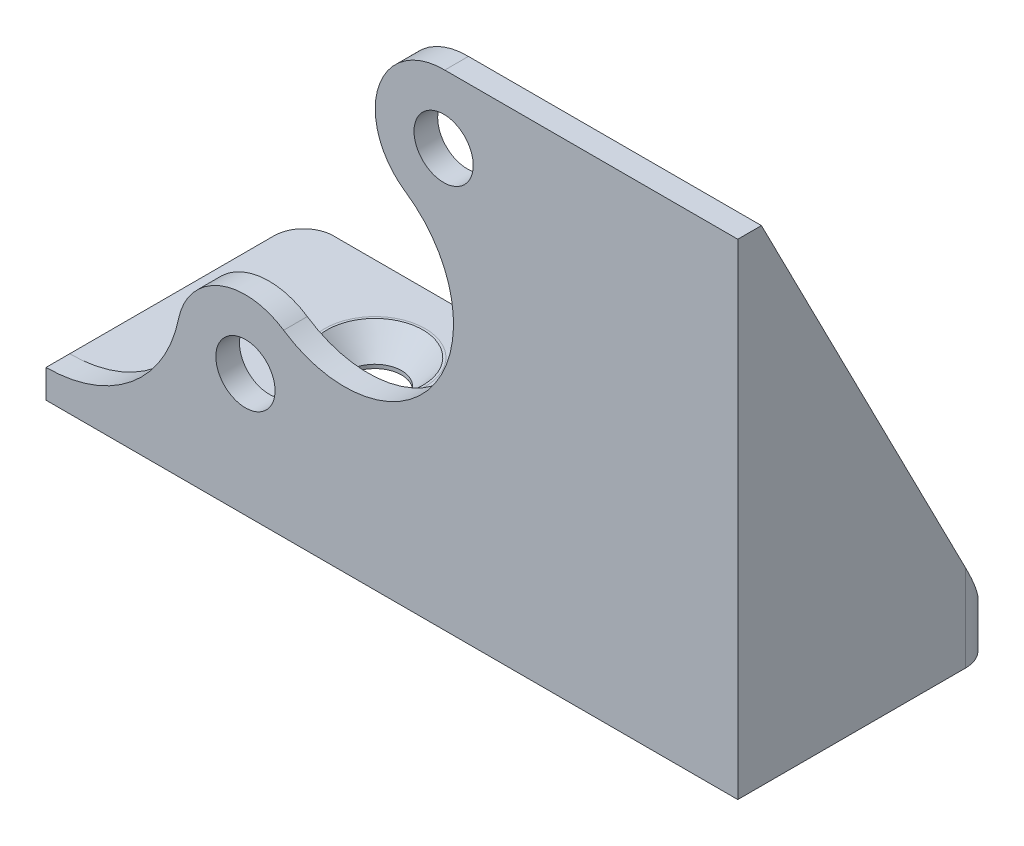
SolidWorks part; units mm, degrees
material "UNS A97075 7075-T651 2.501–3.000 in plate (F_ty = 56 ksi)"
ref_plane "Front Plane" through (0, 0, 0) normal (0, 0, 1) x (1, 0, 0)
ref_plane "Top Plane" through (0, 0, 0) normal (0, 1, 0) x (1, 0, 0)
ref_plane "Right Plane" through (0, 0, 0) normal (1, 0, 0) x (0, 0, -1)
sketch "Sketch2" plane through (0, 0, 0) normal (0, 0, 1) x (1, 0, 0)
  line L1 (0, 0) -> (101.6, 0)
  line L2 (0, 0) -> (0, 127)
  line L3 (0, 127) -> (101.6, 127)
  line L4 (101.6, 0) -> (101.6, 127)
  dimension "D1" = 101.6
  dimension "D2" = 127
extrude "Boss-Extrude1" add sketch "Sketch2" along normal blind 3.175
sketch "Sketch3" [suppressed] plane through (0, 0, 3.175) normal (0, 0, 1) x (1, 0, 0)
  line L0 (101.6, 0) -> (101.6, 127) construction
  line L1 (0, 0) -> (101.6, 0)
  line L2 (0, 0) -> (0, 12.1088)
  line L3 (0, 12.1088) -> (101.6, 12.1088)
  line L4 (101.6, 0) -> (101.6, 12.1088)
extrude "Boss-Extrude2" [suppressed] add sketch "Sketch3" along normal blind 25.4
sketch "Sketch5" plane through (0, 0, 0) normal (0, 0, -1) x (-1, 0, 0)
  line L0 (-58.5712, 65.1526) -> (-81.5862, 65.1526)
  line L1 (-81.5862, 0) -> (-97.9068, 0)
  line L2 (-81.5862, 0) -> (-5.0343, 0)
  line L3 (-5.0343, 0) -> (-5.0343, 3.81)
  line L4 (0, 0) -> (-101.6, 0) construction
  line L5 (-81.5862, 0) -> (-81.5862, 65.1526) construction
  line L6 (-97.9068, 0) -> (-97.9068, 65.1526)
  line L7 (-97.9068, 65.1526) -> (-81.5862, 65.1526)
  line L8 (0, 127) -> (0, 0) construction
  line L9 (-4.9708, 0.0028) -> (-4.9708, -2.9972) construction
  line L10 (-101.6, 0) -> (-101.6, 127) construction
  line L11 (-97.9708, -2.9972) -> (-97.9708, 0.0028) construction
  circle A12 centre (-58.4162, 55.9739) radius 3.9751
  arc A13 (-53.2878, 48.36) -> (-58.5712, 65.1526) centre (-58.4162, 55.9739) ccw
  arc A14 (-53.2878, 48.36) -> (-36.9387, 24.0877) centre (-45.1132, 36.2238) ccw
  arc A15 (-22.8172, 18.3173) -> (-36.9387, 24.0877) centre (-31.8102, 16.4738) ccw
  circle A16 centre (-31.8102, 16.4738) radius 3.9751
  arc A17 (-5.0343, 3.81) -> (-22.8172, 18.3173) centre (-5.0343, 21.9627) cw
  line M8 (0, 0) -> (0, 127)
  line M9 (0, 127) -> (-101.6, 127)
  line M10 (-101.6, 127) -> (-101.6, 0)
  line M11 (-101.6, 0) -> (0, 0)
  dimension "D1" = 3.81
  dimension "D2" = 76.5519
  dimension "D3" = 92.8726
  dimension "D5" = 5.0343
  dimension "D6" = 0.0635
  dimension "D7" = 3.6932
  dimension "D8" = 0.0639
extrude "Cut-Extrude1" cut sketch "Sketch5" against normal blind 3.175 contours A17 L3 L6 L7 L0 A13 A14 A15 M11 M8 M9 M10 | A12 | A16
sketch "Sketch10" plane through (5.0343, 0, 0) normal (1, 0, 0) x (0, 0, -1)
  line L0 (-3.175, 0) -> (-4.2418, 0)
  line L1 (-4.2418, 0) -> (-4.2418, -2.9972)
  line L2 (-4.2418, -2.9972) -> (-34.5948, -2.9972)
  line L3 (-34.5948, -2.9972) -> (-34.5948, 0)
  line L4 (-34.5948, 0) -> (-4.2418, 0) construction
  line L7 (-3.175, 3.81) -> (-34.5948, 3.81)
  line L8 (-3.175, 3.81) -> (-3.175, 0)
  line L9 (-34.5948, 3.81) -> (-34.5948, 0)
  dimension "D1" = 1.0668
  dimension "D2" = 2.9972
  dimension "D3" = 30.353
  dimension "D4" = 3.81
extrude "Boss-Extrude3" add sketch "Sketch10" along normal up to surface (92.8726 mm away) up to face at (97.9068, 32.5763, 1.5875)
sketch "Sketch11" plane through (97.9068, 0, 0) normal (1, 0, 0) x (0, 0, -1)
  line L1 (-3.175, 3.81) -> (-34.5948, 3.81) construction
  line L3 (-3.175, 65.1526) -> (-3.175, 3.81)
  line L6 (-34.5948, 3.81) -> (-3.175, 3.81)
  line L8 (-34.5948, 3.81) -> (-3.175, 3.81) construction
  line L9 (-34.5948, 3.81) -> (-3.175, 65.1526)
extrude "Boss-Extrude4" add sketch "Sketch11" against normal blind 6.35
sketch "Sketch18" plane through (0, -2.9972, 0) normal (0, -1, 0) x (1, 0, 0)
  circle A2 centre (25.968, 23.2283) radius 3.175
  circle A4 centre (81.868, 23.2283) radius 3.175
extrude "Cut-Extrude3" cut sketch "Sketch18" against normal up to surface (6.8072 mm away) up to face at (48.2956, 3.81, 18.8849)
fillet "Fillet4" radius 4.0005 4 edges at (97.9068, -1.4986, 4.2418) (5.0343, -1.4986, 4.2418) (97.9068, 0.4064, 34.5948) (5.0343, 0.4064, 34.5948)
sketch "Sketch19" plane through (0, 0, 34.5948) normal (0, 0, 1) x (1, 0, 0)
  line L0 (9.0348, 0.0028) -> (93.9063, 0.0028)
  line L1 (9.0348, 3.81) -> (9.0348, -2.9972) construction
  line L2 (93.9063, -2.9972) -> (93.9063, 3.81) construction
  line L3 (93.9063, -2.9972) -> (9.0348, -2.9972) construction
  dimension "D1" = 3
sketch "Sketch20" plane through (97.9068, 0, 0) normal (1, 0, 0) x (0, 0, -1)
  line L0 (-8.2423, 0) -> (-30.7225, 0)
sketch "Sketch22" plane through (5.0343, 0, 0) normal (-1, 0, 0) x (0, 0, 1)
  line L0 (8.2423, 0) -> (30.5943, 0)
  line L1 (30.5943, -2.9972) -> (30.5943, 3.81) construction
fillet "Fillet5" [suppressed] radius 6.35
split line "Split Line1"
split line "Split Line4"
split line "Split Line5"
fillet "Fillet6" [suppressed] radius 6.35
mirror "Mirror5" about plane through (0, 0, 0) normal (0, 0, 1) of bodies 114
sketch "FEA Force Line" plane through (0, 0, -3.175) normal (0, 0, -1) x (-1, 0, 0)
  line L0 (-58.4162, 55.9739) -> (-31.8102, 16.4738)
  line L1 (-45.1132, 36.2238) -> (-57.2494, 28.0493)
  circle A0 centre (-58.4162, 55.9739) radius 3.9751 construction
  circle A2 centre (-31.8102, 16.4738) radius 3.9751 construction
  arc A3 (-53.2878, 48.36) -> (-36.9387, 24.0877) centre (-45.1132, 36.2238) ccw construction
ref_plane "Plane1" through (14.2491, -9.5978, 0) normal (0.8294, -0.5587, 0) x (-0.5587, -0.8294, 0)
ref_plane "Plane2" through (30.8641, 45.8216, 0) normal (0.5587, 0.8294, 0) x (0.8294, -0.5587, 0)
sketch "Sketch25" plane through (0, 0, 0) normal (0, 0, 1) x (1, 0, 0)
  line L0 (105.4755, -15.2416) -> (106.8408, 71.8338)
  line L1 (105.4755, -15.2416) -> (-9.9073, -13.4325)
  line L2 (106.8408, 71.8338) -> (-8.542, 73.6429)
  line L3 (-9.9073, -13.4325) -> (-8.542, 73.6429)
extrude "Cut-Extrude4" cut sketch "Sketch25" along normal up to surface (34.5948 mm away) up to face at (51.4706, -1.4972, 34.5948)
sketch "Sketch28" plane through (0, -2.9972, 0) normal (0, -1, 0) x (1, 0, 0)
  line L4 (5.0343, -8.2423) -> (5.0343, -30.5943)
  line L6 (9.0348, -34.5948) -> (93.9063, -34.5948)
  line L7 (93.9063, -4.2418) -> (9.0348, -4.2418)
  line L11 (93.9063, -4.2418) -> (9.0348, -4.2418)
  line L13 (97.9068, -30.5943) -> (97.9068, -8.2423)
  line L15 (9.0348, -34.5948) -> (93.9063, -34.5948)
  line L16 (5.0343, -8.2423) -> (5.0343, -30.5943)
  line L17 (97.9068, -30.5943) -> (97.9068, -8.2423)
  arc A5 (5.0343, -30.5943) -> (9.0348, -34.5948) centre (9.0348, -30.5943) ccw
  arc A6 (5.0343, -30.5943) -> (9.0348, -34.5948) centre (9.0348, -30.5943) ccw
  arc A7 (93.9063, -34.5948) -> (97.9068, -30.5943) centre (93.9063, -30.5943) ccw
  arc A12 (93.9063, -34.5948) -> (97.9068, -30.5943) centre (93.9063, -30.5943) ccw
  arc A13 (97.9068, -8.2423) -> (93.9063, -4.2418) centre (93.9063, -8.2423) ccw
  arc A14 (97.9068, -8.2423) -> (93.9063, -4.2418) centre (93.9063, -8.2423) ccw
  arc A15 (9.0348, -4.2418) -> (5.0343, -8.2423) centre (9.0348, -8.2423) ccw
  arc A16 (9.0348, -4.2418) -> (5.0343, -8.2423) centre (9.0348, -8.2423) ccw
  dimension "D1" = 0
extrude "Cut-Extrude5" cut sketch "Sketch28" against normal up to surface (2.9972 mm away) up to face at (51.4706, 0, -3.8852)
sketch "Sketch31" plane through (0, 3.81, 0) normal (0, 1, 0) x (1, 0, 0)
  line L4 (91.5568, 34.5948) -> (9.0348, 34.5948)
  line L6 (5.0343, 30.5943) -> (5.0343, 3.175)
  line L12 (5.0343, 30.5943) -> (5.0343, 3.175)
  line L14 (5.0343, 3.175) -> (91.5568, 3.175)
  line L16 (91.5568, 34.5948) -> (9.0348, 34.5948)
  line L22 (5.0343, 3.175) -> (91.5568, 3.175)
  line L24 (91.5568, 3.175) -> (91.5568, 34.5948)
  line L25 (91.5568, 3.175) -> (91.5568, 34.5948)
  circle A0 centre (81.868, 23.2283) radius 3.175 construction
  arc A1 (9.0348, 34.5948) -> (5.0343, 30.5943) centre (9.0348, 30.5943) ccw
  arc A3 (9.0348, 34.5948) -> (5.0343, 30.5943) centre (9.0348, 30.5943) ccw
  circle A4 centre (25.968, 23.2283) radius 3.175 construction
  circle A5 centre (81.868, 23.2283) radius 3.175
  circle A6 centre (25.968, 23.2283) radius 3.175
  dimension "D1" = 0
fillet "Fillet7" radius 6.35 1 edges at (91.5568, 3.81, -18.8849)
sketch "Sketch33" plane through (0, 3.81, 0) normal (0, 1, 0) x (1, 0, 0)
  circle A0 centre (25.968, 23.2283) radius 6.7437
  circle A1 centre (81.868, 23.2283) radius 6.7437
  dimension "D1" = 13.4874
split line "Split Line6"
hole_wizard "CSK for 1/4 Flat Head Machine Screw (100)1" positions "Sketch34" profile "Sketch35" countersink size "1/4" standard "ANSI Inch" end condition through all
sketch "Sketch34" plane through (0, 3.81, 0) normal (0, 1, 0) x (1, 0, 0)
  point P0 (25.968, 23.2283)
  point P3 (25.968, 23.2283)
  point P7 (81.868, 23.2283)
sketch "Sketch35" plane through (25.968, 3.81, -23.2283) normal (1, 0, 0) x (0, 0, 1)
  line L0 (0, 0) -> (0, 3.81)
  line L1 (0, 3.81) -> (3.5712, 3.81)
  line L2 (3.5712, 3.81) -> (3.5712, 3.2989)
  line L3 (3.5712, 3.2989) -> (6.4389, 0)
  line L5 (6.4389, 0) -> (0, 0)
  line L6 (-3.5712, 3.2989) -> (-6.4389, 0) construction
  line L11 (0, -6.35) -> (0, 107.95) construction
  dimension "Thru Hole Dia." = 7.1425
  dimension "Thru Hole Depth" = 3.81
  dimension "Near C'Sink Dia." = 12.8778
  dimension "Near C'Sink Angle" = 82
sketch "Sketch36" plane through (0, 3.81, 0) normal (0, 1, 0) x (1, 0, 0)
  circle A0 centre (81.868, 23.2283) radius 6.4389
  arc A1 (85.2068, 28.7339) -> (85.2068, 17.7227) centre (81.868, 23.2283) ccw construction
extrude "Cut-Extrude6" cut sketch "Sketch36" along normal blind 2.54
